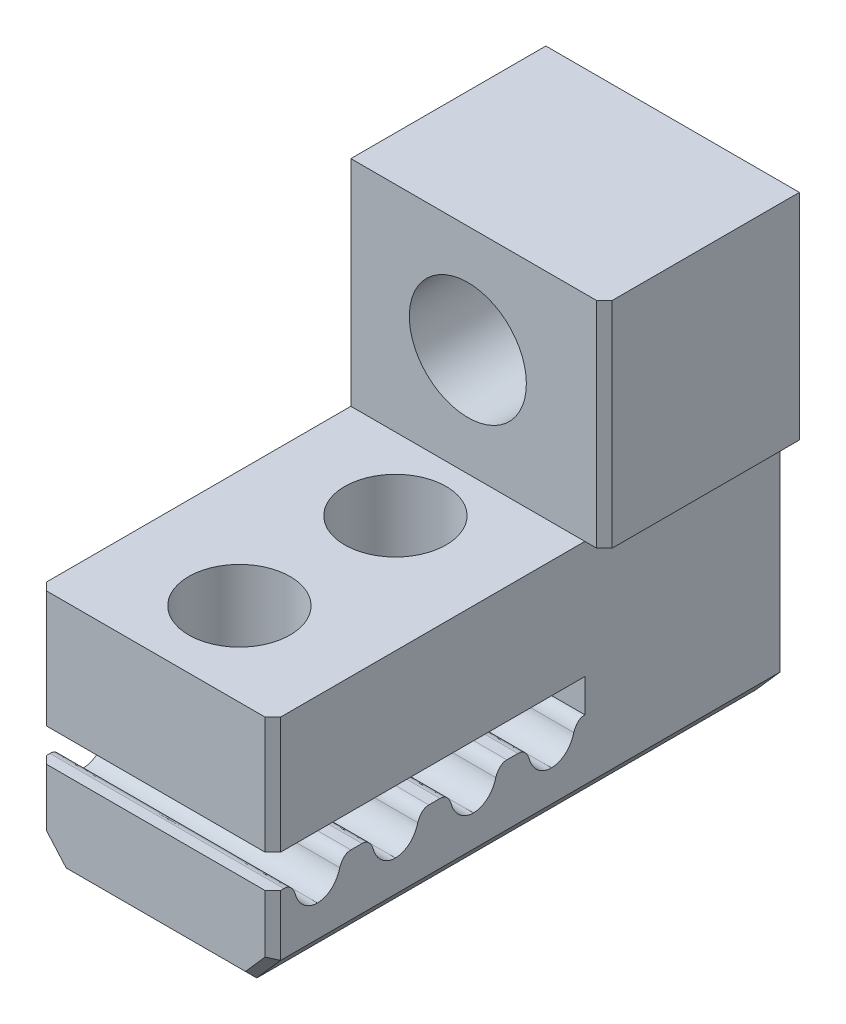
SolidWorks part; units mm, degrees
ref_plane "Front Plane" through (0, 0, 0) normal (0, 0, 1) x (1, 0, 0)
ref_plane "Top Plane" through (0, 0, 0) normal (0, 1, 0) x (1, 0, 0)
ref_plane "Right Plane" through (0, 0, 0) normal (1, 0, 0) x (0, 0, -1)
sketch "Sketch1" plane through (0, 0, 0) normal (0, 0, 1) x (1, 0, 0)
  line L0 (3, 3.05) -> (3, -2.2538)
  line L1 (-3, 3.05) -> (-3, -2.2538)
  line L7 (-3, 3.05) -> (3, 3.05)
  line L13 (-3, -2.2538) -> (-2.3882, -2.95)
  line L14 (3, -2.2538) -> (2.3882, -2.95)
  line L16 (-2.3882, -2.95) -> (2.3882, -2.95)
extrude "Boss-Extrude1" add sketch "Sketch1" along normal blind 13
sketch "Sketch6" plane through (0, 3.05, 0) normal (0, 1, 0) x (1, 0, 0)
  line L1 (-3, 0) -> (3, 0)
  line L2 (-3, 0) -> (-3, -5)
  line L3 (-3, -5) -> (3, -5)
  line L4 (3, 0) -> (3, -5)
  line L7 (3, 0) -> (-3, 0) construction
  line L9 (3, -13) -> (3, 0) construction
  line L10 (-3, -13) -> (-3, 0) construction
extrude "Boss-Extrude4" add sketch "Sketch6" along normal blind 5.6
sketch "Sketch16" plane through (0, 3.05, 0) normal (0, 1, 0) x (1, 0, 0)
  line L4 (3, -5) -> (-3, -5)
  line L5 (-3, -5) -> (-3, -13)
  line L6 (-3, -13) -> (3, -13)
  line L7 (3, -13) -> (3, -5)
  line L8 (3, -5) -> (-3, -5)
  line L9 (-3, -5) -> (-3, -13)
  line L10 (-3, -13) -> (3, -13)
  line L11 (3, -13) -> (3, -5)
  dimension "D1" = 0
extrude "Boss-Extrude5" add sketch "Sketch16" along normal blind 0.1
sketch "Sketch18" plane through (0, 0, 0) normal (1, 0, 0) x (0, 0, -1)
  line L0 (-8.8572, -0.0702) -> (-12.8572, -0.0702)
  line L2 (-12.8572, -0.7) -> (-12.7144, -0.7)
  line L3 (-11, -0.7) -> (-10.8572, -0.7)
  line L4 (-10.8572, -0.7) -> (-10.7144, -0.7)
  line L5 (-9, -0.7) -> (-8.8572, -0.7)
  line L6 (-8.8572, -0.7) -> (-8.7144, -0.7)
  line L7 (-7, -0.7) -> (-6.8572, -0.7)
  line L8 (-6.8572, -0.7) -> (-6.7144, -0.7)
  line L9 (-5, -0.0702) -> (-5, -0.7)
  line L11 (-5, -0.0702) -> (-8.8572, -0.0702)
  line L12 (-13, -2.95) -> (0, -2.95) construction
  line L13 (-5.8572, -1.45) -> (-5, -1.45) construction
  line L14 (-5, -1.45) -> (-11.8572, -1.45) construction
  line L15 (-5, 3.15) -> (-5, -1.45) construction
  line L16 (-5, -0.7) -> (-5, -1.45) construction
  line L17 (-12.8572, -0.0702) -> (-13, -0.0702)
  line L20 (-13, -0.0702) -> (-13, -0.7)
  line L22 (-12.8572, -0.7) -> (-13, -0.7)
  spline S0 degree 2 poles (-12.7144, -0.7) (-12.5198, -0.7) (-12.43, -0.9509) knots 0.103448 0.103448 0.103448 0.137931 0.137931 0.137931
  spline S1 degree 3 poles (-12.43, -0.9509) (-12.3594, -1.2388) (-12.13, -1.45) (-11.8572, -1.45) knots 0.137931 0.137931 0.137931 0.137931 0.172414 0.172414 0.172414 0.172414
  spline S2 degree 3 poles (-11.8572, -1.45) (-11.5844, -1.45) (-11.355, -1.2388) (-11.2844, -0.9509) knots 0.172414 0.172414 0.172414 0.172414 0.206897 0.206897 0.206897 0.206897
  spline S3 degree 2 poles (-11.2844, -0.9509) (-11.1946, -0.7) (-11, -0.7) knots 0.206897 0.206897 0.206897 0.241379 0.241379 0.241379
  spline S4 degree 2 poles (-10.7144, -0.7) (-10.5198, -0.7) (-10.43, -0.9509) knots 0.310345 0.310345 0.310345 0.344828 0.344828 0.344828
  spline S5 degree 3 poles (-10.43, -0.9509) (-10.3594, -1.2388) (-10.13, -1.45) (-9.8572, -1.45) knots 0.344828 0.344828 0.344828 0.344828 0.37931 0.37931 0.37931 0.37931
  spline S6 degree 3 poles (-9.8572, -1.45) (-9.5844, -1.45) (-9.355, -1.2388) (-9.2844, -0.9509) knots 0.37931 0.37931 0.37931 0.37931 0.413793 0.413793 0.413793 0.413793
  spline S7 degree 2 poles (-9.2844, -0.9509) (-9.1946, -0.7) (-9, -0.7) knots 0.413793 0.413793 0.413793 0.448276 0.448276 0.448276
  spline S8 degree 2 poles (-8.7144, -0.7) (-8.5198, -0.7) (-8.43, -0.9509) knots 0.517241 0.517241 0.517241 0.551724 0.551724 0.551724
  spline S9 degree 3 poles (-8.43, -0.9509) (-8.3594, -1.2388) (-8.13, -1.45) (-7.8572, -1.45) knots 0.551724 0.551724 0.551724 0.551724 0.586207 0.586207 0.586207 0.586207
  spline S10 degree 3 poles (-7.8572, -1.45) (-7.5844, -1.45) (-7.355, -1.2388) (-7.2844, -0.9509) knots 0.586207 0.586207 0.586207 0.586207 0.62069 0.62069 0.62069 0.62069
  spline S11 degree 2 poles (-7.2844, -0.9509) (-7.1946, -0.7) (-7, -0.7) knots 0.62069 0.62069 0.62069 0.655172 0.655172 0.655172
  spline S12 degree 2 poles (-6.7144, -0.7) (-6.5198, -0.7) (-6.43, -0.9509) knots 0.724138 0.724138 0.724138 0.758621 0.758621 0.758621
  spline S13 degree 3 poles (-6.43, -0.9509) (-6.3594, -1.2388) (-6.13, -1.45) (-5.8572, -1.45) knots 0.758621 0.758621 0.758621 0.758621 0.793103 0.793103 0.793103 0.793103
  spline S14 degree 3 poles (-5.8572, -1.45) (-5.5844, -1.45) (-5.355, -1.2388) (-5.2844, -0.9509) knots 0.793103 0.793103 0.793103 0.793103 0.827586 0.827586 0.827586 0.827586
  spline S15 degree 2 poles (-5.2844, -0.9509) (-5.1946, -0.7) (-5, -0.7) knots 0.827586 0.827586 0.827586 0.862069 0.862069 0.862069
  dimension "D1" = 1.5
  dimension "D2" = 1.3798
extrude "Cut-Extrude6" cut sketch "Sketch18" against normal blind 3.6 and the other way blind 4
sketch "Sketch15" plane through (0, 8.65, 0) normal (0, 1, 0) x (1, 0, 0)
  line L0 (0, -13) -> (0, -5) construction
  line L1 (-3, -13) -> (3, -13) construction
  line L2 (-3, -5) -> (3, -5) construction
  line L3 (2.008, -10.7144) -> (2.008, -11) construction
  line L4 (3, -10.7144) -> (-3, -10.7144) construction
  line L5 (3, -11) -> (-3, -11) construction
  line L6 (2.008, -10.8572) -> (0, -10.8572) construction
  line L7 (1.0382, -6.7144) -> (1.0382, -7) construction
  line L8 (3, -6.7144) -> (-3, -6.7144) construction
  line L9 (3, -7) -> (-3, -7) construction
  line L10 (1.0382, -6.8572) -> (0, -6.8572) construction
  circle A0 centre (0, -6.8572) radius 1.5 construction
  circle A1 centre (0, -10.8572) radius 1.5 construction
  circle A2 centre (0, -10.8572) radius 1.3
  circle A4 centre (0, -6.8572) radius 1.3
  dimension "D1" = 2.6
  dimension "D2" = 2.6
extrude "Cut-Extrude7" cut sketch "Sketch15" against normal up to surface (8.7202 mm away) up to face at (0, -0.0702, 9)
sketch "Sketch19" plane through (0, -0.0702, 0) normal (0, -1, 0) x (1, 0, 0)
  line L4 (-3, 13) -> (-3, 5)
  line L5 (-3, 5) -> (3, 5)
  line L6 (3, 5) -> (3, 13)
  line L7 (3, 13) -> (-3, 13)
  line L8 (-3, 13) -> (-3, 5)
  line L9 (-3, 5) -> (3, 5)
  line L10 (3, 5) -> (3, 13)
  line L11 (3, 13) -> (-3, 13)
  circle A0 centre (0, 10.8572) radius 1.3 construction
  circle A1 centre (0, 6.8572) radius 1.3 construction
  circle A2 centre (0, 10.8572) radius 1.3
  circle A3 centre (0, 6.8572) radius 1.3
  dimension "D1" = 0
extrude "Cut-Extrude8" cut sketch "Sketch19" against normal blind 0.2202
sketch "Sketch12" plane through (0, 0, 5) normal (0, 0, 1) x (1, 0, 0)
  line L0 (-3, 5.9) -> (0, 5.9) construction
  line L1 (-3, 8.65) -> (-3, 3.15) construction
  line L2 (0, 5.9) -> (0, 8.65) construction
  line L3 (-3, 8.65) -> (3, 8.65) construction
  circle A0 centre (0, 5.9) radius 1.5 construction
  circle A1 centre (0, 5.9) radius 1.5
  dimension "D1" = 3
extrude "Cut-Extrude5" cut sketch "Sketch12" against normal blind 6
chamfer "Chamfer1" distance 0.2 angle 45 7 edges at (-3, 1.65, 13) (3, 1.65, 13) (3, -1.4769, 13) (2.6941, -2.6019, 13) (-3, -1.4769, 13) (-2.6941, -2.6019, 13) (0, -2.95, 13)
sketch "Sketch20" plane through (3, 0, 0) normal (1, 0, 0) x (0, 0, -1)
  line L1 (-5, 3.15) -> (0, 3.15)
  line L2 (-5, 3.15) -> (-5, 8.65)
  line L3 (-5, 8.65) -> (0, 8.65)
  line L4 (0, 3.15) -> (0, 8.65)
extrude "Boss-Extrude6" add sketch "Sketch20" along normal blind 0.5
sketch "Sketch21" plane through (-3, 0, 0) normal (-1, 0, 0) x (0, 0, 1)
  line L1 (5, 3.15) -> (0, 3.15)
  line L2 (5, 3.15) -> (5, 8.65)
  line L3 (5, 8.65) -> (0, 8.65)
  line L4 (0, 3.15) -> (0, 8.65)
extrude "Boss-Extrude7" add sketch "Sketch21" along normal blind 0.5
chamfer "Chamfer2" distance 0.2 angle 45 2 edges at (-3.5, 5.9, 5) (3.5, 5.9, 5)
sketch "Croquis1" plane through (-3.5, 0, 0) normal (-1, 0, 0) x (0, 0, 1)
  line L1 (5, 3.15) -> (0, 3.15)
  line L2 (5, 3.15) -> (5, 8.65)
  line L3 (5, 8.65) -> (0, 8.65)
  line L4 (0, 3.15) -> (0, 8.65)
extrude "Cortar-Extruir1" cut sketch "Croquis1" against normal up to surface (0.5 mm away) up to face at (-3, -0.5166, 8.3898)
